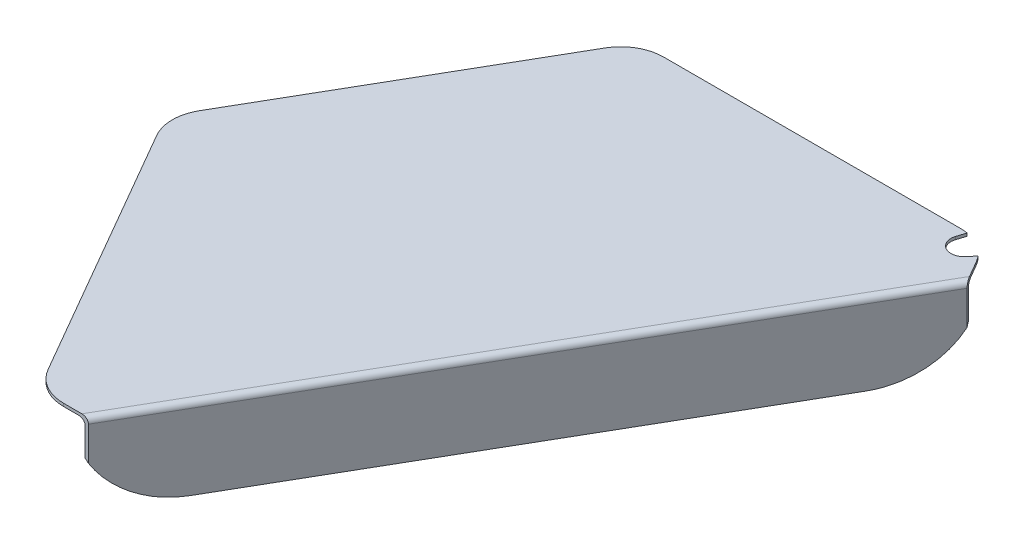
SolidWorks part; units mm, degrees
ref_plane "Alzado" through (0, 0, 0) normal (0, 0, 1) x (1, 0, 0)
ref_plane "Planta" through (0, 0, 0) normal (0, 1, 0) x (1, 0, 0)
ref_plane "Vista lateral" through (0, 0, 0) normal (1, 0, 0) x (0, 0, -1)
sketch "Croquis1" plane through (0, 0, 0) normal (0, 1, 0) x (1, 0, 0)
  line L0 (-63.1182, -98.8234) -> (-115.0797, -8.8234)
  line L1 (-115.0797, 6.1766) -> (-63.1182, 96.1766)
  line L2 (-50.1278, 103.6766) -> (53.7952, 103.6766)
  line L3 (71.1157, 88.6766) -> (66.7856, 96.1766)
  line L4 (-41.4676, -106.3234) -> (-50.1278, -106.3234)
  line L5 (103.3607, 144.5264) -> (-41.4676, -106.3234)
  line L11 (56.3411, 103.4023) -> (55.3769, 100.4105)
  line L12 (63.4143, 96.2118) -> (65.207, 98.3292)
  line L13 (56.3584, 103.456) -> (55.3769, 100.4105)
  line L14 (63.4143, 96.2118) -> (65.242, 98.3705)
  arc A0 (-115.0797, 6.1766) -> (-115.0797, -8.8234) centre (-102.0893, -1.3234) ccw
  arc A1 (-50.1278, 103.6766) -> (-63.1182, 96.1766) centre (-50.1278, 88.6766) ccw
  arc A2 (66.7856, 96.1766) -> (65.242, 98.3705) centre (53.7952, 88.6766) ccw
  arc A3 (-63.1182, -98.8234) -> (-50.1278, -106.3234) centre (-50.1278, -91.3234) ccw
  arc A4 (56.3584, 103.456) -> (53.7952, 103.6766) centre (53.7952, 88.6766) ccw
  arc A8 (55.3769, 100.4105) -> (63.4143, 96.2118) centre (59.7551, 98.9995) ccw
  arc A9 (55.3769, 100.4105) -> (63.4143, 96.2118) centre (59.7551, 98.9995) ccw
  dimension "D1" = 103.923
  dimension "D2" = 103.923
  dimension "D3" = 103.923
  dimension "D4" = 120
  dimension "D5" = 0.1
extrude "Saliente-Extruir1" add sketch "Croquis1" along normal blind 1 contours L0 A3 L4 L5 L3 A2 L2 A1 L1 A0
sketch "Croquis2" plane through (0, 0, 0) normal (0, -1, 0) x (1, 0, 0)
  line L0 (71.1157, -88.6766) -> (-41.4676, 106.3234) construction
  line L1 (71.1157, -88.6766) -> (-41.4676, 106.3234)
  line L3 (-41.4676, 106.3234) -> (-50.1278, 106.3234) construction
  line L4 (71.1157, -88.6766) -> (66.7856, -96.1766) construction
  line L5 (71.1157, -88.6766) -> (70.5384, -89.6766)
  line L6 (-42.6223, 106.3234) -> (70.5384, -89.6766)
  line L7 (-41.4676, 106.3234) -> (-42.6223, 106.3234)
  line L8 (71.1157, -88.6766) -> (70.5384, -89.6766)
  line M19 (66.7856, -96.1766) -> (71.1157, -88.6766)
  line M20 (71.1157, -88.6766) -> (-41.4676, 106.3234)
  line M21 (-41.4676, 106.3234) -> (-50.1278, 106.3234)
  dimension "D1" = 1
extrude "Saliente-Extruir2" add sketch "Croquis2" along normal blind 27.5 contours L6 M21 M19 M20
fillet "Redondeo1" radius 2 2 edges at (14.8241, 1, 8.8234) (13.9581, 0, 8.3234)
sketch "Croquis3" plane through (14.9387, 0, 8.6249) normal (0.866, 0, 0.5) x (0.5, 0, -0.866)
  line L13 (-117.1427, 2.5779) -> (-128.5092, -12.943)
  line L15 (-65.1811, 2.5779) -> (-117.1427, 2.5779)
  line L16 (-86.8318, -27.4221) -> (-43.5305, -27.4221)
  line L19 (116.6842, 2.5779) -> (140.2294, -2.7085)
  line L20 (81.1699, 1.0295) -> (64.6938, 1.0295)
  line L21 (81.434, 2.5779) -> (81.2045, 2.5779)
  line L22 (94.4529, 1.0667) -> (82.7308, 1.0667)
  line L23 (96.1849, 2.5779) -> (95.8157, 2.5779)
  line L24 (111.4176, -1.7139) -> (97.4176, -1.7139)
  line L25 (116.6842, 2.5779) -> (113.1849, 2.5779)
  line L26 (67.7238, -27.4221) -> (86.3733, -27.4221)
  line L34 (86.3733, -27.4221) -> (-86.8318, -27.4221)
  line L35 (140.2294, -2.7085) -> (121.2929, -43.8284)
  line L36 (121.2929, -43.8284) -> (-113.2262, -43.8284)
  line L37 (-113.2262, -43.8284) -> (-128.5092, -12.943)
  line L85 (54.2238, -27.4221) -> (67.7238, -27.4221)
  line L106 (64.4609, -2.0732) -> (77.3904, -2.0732)
  line L112 (51.7238, -27.4221) -> (54.2238, -27.4221)
  line L114 (43.072, -27.4221) -> (51.7238, -27.4221)
  line L116 (77.2672, -2.9032) -> (64.3583, -2.9032)
  ellipse E2 centre (-86.8318, 2.5779) end of major axis (-56.5209, 2.5779) minor radius 30 (-117.1427, 2.5779) -> (-86.8318, -27.4221) ccw
  ellipse E3 centre (-43.5305, 2.5779) end of major axis (-43.5305, 32.5779) minor radius 21.6506 (-65.1811, 2.5779) -> (-43.5305, -27.4221) ccw
  ellipse E4 centre (-86.8318, 2.5779) end of major axis (-56.5209, 2.5779) minor radius 30 (-117.1427, 2.5779) -> (-86.8318, -27.4221) ccw
  ellipse E5 centre (43.072, 2.5779) end of major axis (43.072, -27.4221) minor radius 21.6506 (64.4609, -2.0732) -> (64.6938, 1.0295) ccw
  ellipse E6 centre (55.2238, 2.5779) end of major axis (55.2238, 32.5779) minor radius 25.9808 (81.1699, 1.0295) -> (81.2045, 2.5779) ccw
  ellipse E7 centre (70.2041, 2.5779) end of major axis (70.2041, -27.4221) minor radius 25.9808 (96.1533, 1.0986) -> (96.1849, 2.5779) ccw
  ellipse E8 centre (87.2041, 2.5779) end of major axis (87.2041, 32.5779) minor radius 25.9808 (113.1533, 1.0986) -> (113.1849, 2.5779) ccw
  ellipse E9 centre (86.3733, 2.5779) end of major axis (56.0624, 2.5779) minor radius 30 (86.3733, -27.4221) -> (116.6842, 2.5779) ccw
  ellipse E14 centre (86.3733, 2.5779) end of major axis (56.0624, 2.5779) minor radius 30 (86.3733, -27.4221) -> (116.6842, 2.5779) ccw
  ellipse E56 centre (43.072, 2.5779) end of major axis (43.072, -27.4221) minor radius 21.6506 (43.072, -27.4221) -> (64.3583, -2.9032) ccw
  ellipse E58 centre (51.7238, 2.5779) end of major axis (51.7238, -27.4221) minor radius 25.9808 (77.2672, -2.9032) -> (77.3904, -2.0732) ccw
  spline S4 degree 3 poles (405.3234, 947.6042) (131.5439, 227.8743) (93.0956, -4.4727) (82.2757, 1.1997) (82.213, 1.2416) (82.0926, 1.3406) (82.0345, 1.3977) (81.8666, 1.5922) (81.7619, 1.755) (76.4014, 12.7281) (108.9737, 114.3215) (745.6845, -744.9191) knots -20.98117 -20.98117 -20.98117 -20.98117 0.25 0.25 0.375 0.375 0.5 0.5 0.75 0.75 15.194014 15.194014 15.194014 15.194014 only from (82.7308, 1.0667) to (81.434, 2.5779)
  spline S5 degree 3 poles (-605.8876, 715.0462) (51.211, 109.717) (101.56, 13.3711) (95.519, 1.8495) (95.4656, 1.7612) (95.3546, 1.6013) (95.2967, 1.5289) (95.1162, 1.3341) (94.9859, 1.2335) (87.3216, -2.632) (67.4533, 99.3406) (851.6696, 654.2161) knots -14.9545 -14.9545 -14.9545 -14.9545 0.25 0.25 0.375 0.375 0.5 0.5 0.75 0.75 15.069178 15.069178 15.069178 15.069178 only from (95.8157, 2.5779) to (94.4529, 1.0667)
  spline S6 degree 3 poles (-575.0249, 738.4352) (146.4589, 97.2884) (103.5665, -7.0621) (96.7205, -1.376) (96.5772, -1.1745) (96.4061, -0.7925) (96.3551, -0.6494) (96.2701, -0.3434) (96.2356, -0.1806) (96.1826, 0.1651) (96.1644, 0.3484) (95.132, 20.8691) (197.6701, 85.5975) (964.274, 497.4483) knots -10.111144 -10.111144 -10.111144 -10.111144 0.25 0.25 0.5 0.5 0.625 0.625 0.75 0.75 0.875 0.875 14.633329 14.633329 14.633329 14.633329 only from (97.4176, -1.7139) to (96.1533, 1.0986)
  spline S7 degree 3 poles (-852.6416, 260.4037) (-36.0411, 78.8187) (116.7785, 22.2802) (113.0615, 0.3426) (113.0187, 0.1617) (112.9144, -0.1817) (112.8519, -0.347) (112.7115, -0.6538) (112.6344, -0.7938) (112.4683, -1.0486) (112.3784, -1.1639) (112.1941, -1.3608) (112.0993, -1.4436) (111.9047, -1.5781) (111.8056, -1.6292) (102.0592, -5.0036) (98.994, 154.29) (198.4294, 994.4873) knots -14.409742 -14.409742 -14.409742 -14.409742 0.125 0.125 0.25 0.25 0.375 0.375 0.5 0.5 0.625 0.625 0.75 0.75 0.875 0.875 13.241934 13.241934 13.241934 13.241934 only from (113.1533, 1.0986) to (111.4176, -1.7139)
  dimension "D3" = 0
  dimension "D4" = 0
extrude "Cortar-Extruir1" cut sketch "Croquis3" against normal blind 3
